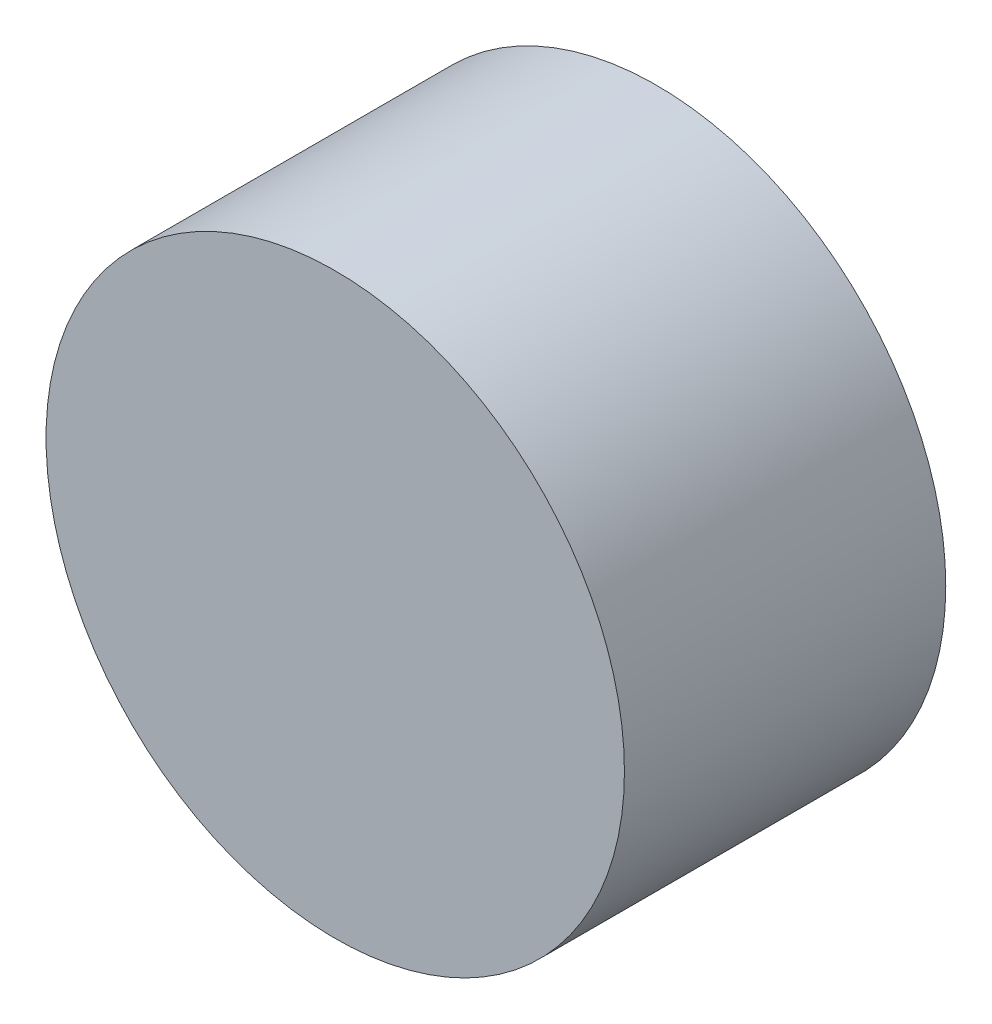
SolidWorks part; units mm, degrees
ref_plane "前视基准面" through (0, 0, 0) normal (0, 0, 1) x (1, 0, 0)
ref_plane "上视基准面" through (0, 0, 0) normal (0, 1, 0) x (1, 0, 0)
ref_plane "右视基准面" through (0, 0, 0) normal (1, 0, 0) x (0, 0, -1)
sketch "草图1" plane through (0, 0, 0) normal (0, 0, 1) x (1, 0, 0)
  circle A0 centre (0, 0) radius 18
  dimension "D1" = 36
extrude "凸台-拉伸1" add sketch "草图1" along normal blind 20
scale "缩放比例1" scale about centroid uniform scaling yes scale factor 0.8
